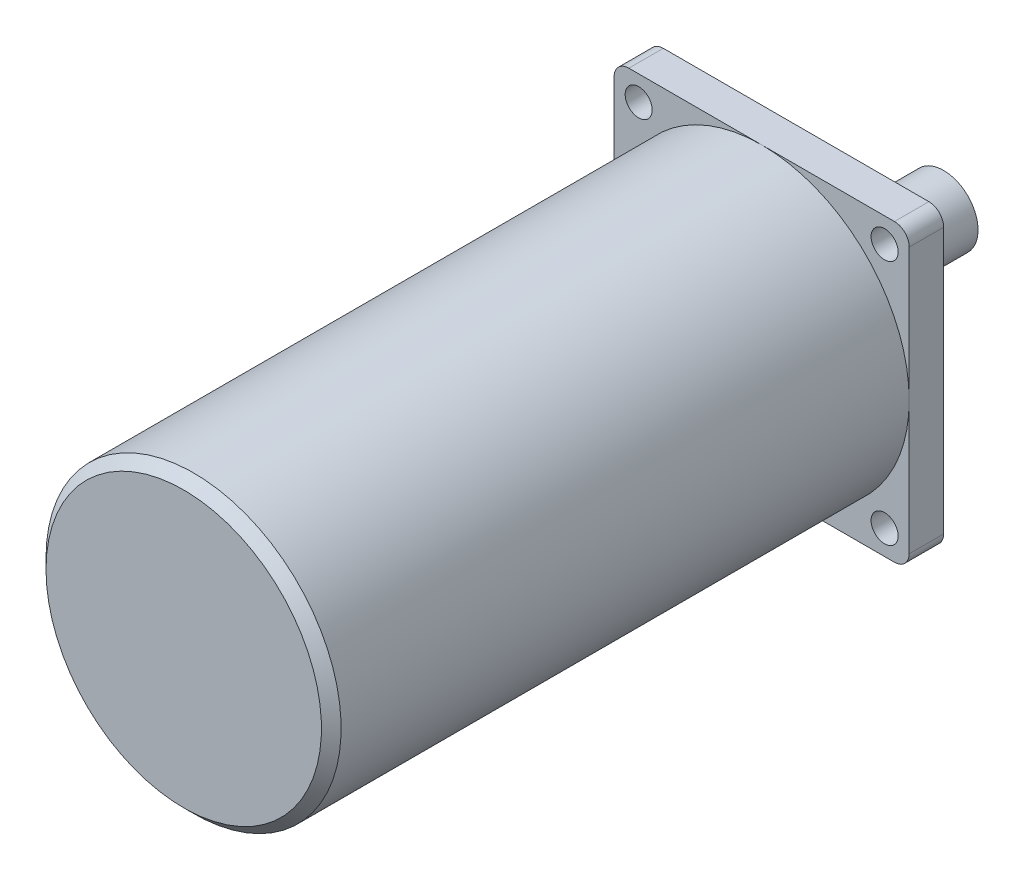
SolidWorks part; units mm, degrees
ref_plane "前基準面" through (0, 0, 0) normal (0, 0, 1) x (1, 0, 0)
ref_plane "上基準面" through (0, 0, 0) normal (0, 1, 0) x (1, 0, 0)
ref_plane "右基準面" through (0, 0, 0) normal (1, 0, 0) x (0, 0, -1)
sketch "草圖1" plane through (0, 0, 0) normal (0, 0, 1) x (1, 0, 0)
  line L1 (0, 0) -> (60, 0)
  line L2 (0, 0) -> (0, 60)
  line L3 (0, 60) -> (60, 60)
  line L4 (60, 0) -> (60, 60)
  dimension "D1" = 60
extrude "伸長1" add sketch "草圖1" along normal blind 124.5
sketch "草圖2" plane through (0, 0, 0) normal (0, 0, -1) x (-1, 0, 0)
  line L0 (-30, 60) -> (-30, 0) construction
  line L1 (-60, 60) -> (0, 60) construction
  line L2 (0, 0) -> (-60, 0) construction
  circle A0 centre (-30, 30) radius 25
  dimension "D1" = 50
extrude "伸長2" add sketch "草圖2" along normal blind 3
sketch "草圖3" plane through (0, 0, -3) normal (0, 0, -1) x (-1, 0, 0)
  circle A0 centre (-30, 30) radius 7
  dimension "D1" = 14
extrude "伸長3" add sketch "草圖3" along normal blind 27
fillet "圓角1" radius 3 4 edges at (60, 0, 62.25) (60, 60, 62.25) (0, 0, 62.25) (0, 60, 62.25)
sketch "草圖4" plane through (0, 0, 124.5) normal (0, 0, 1) x (1, 0, 0)
  line L0 (60, 3) -> (60, 57) construction
  line L1 (3, 0) -> (57, 0) construction
  line L2 (60, 3) -> (60, 30)
  line L3 (30, 0) -> (57, 0)
  line L4 (30, 0) -> (30, 60) construction
  line L5 (57, 60) -> (3, 60) construction
  line L6 (57, 3) -> (30, 30) construction
  arc A0 (57, 0) -> (60, 3) centre (57, 3) ccw construction
  arc A1 (57, 0) -> (60, 3) centre (57, 3) ccw
  arc A2 (30, 0) -> (60, 30) centre (30, 30) ccw
  dimension "D1" = 45
extrude "除料-伸長1" cut sketch "草圖4" against normal offset from surface (117.5 mm away) 7 up to face at (30, 30, 0)
pattern_circular "環狀複製排列1" count 4 every 90 of "除料-伸長1"
chamfer "導角1" distance 2 angle 45 1 edges at (60, 30, 124.5)
sketch "草圖5" plane through (0, 0, 0) normal (0, 0, -1) x (-1, 0, 0)
  line L0 (-30, 0) -> (-30, 60) construction
  line L1 (-3, 0) -> (-57, 0) construction
  line L2 (-57, 60) -> (-3, 60) construction
  line L3 (0, 30) -> (-60, 30) construction
  line L4 (0, 57) -> (0, 3) construction
  line L5 (-60, 3) -> (-60, 57) construction
  circle A0 centre (-5, 5) radius 2.75
  circle A1 centre (-55, 5) radius 2.75
  circle A2 centre (-5, 55) radius 2.75
  circle A3 centre (-55, 55) radius 2.75
  dimension "D1" = 5.5
  dimension "D2" = 50
  dimension "D3" = 50
extrude "除料-伸長2" cut sketch "草圖5" against normal through all
equation "\"D3@草圖5\" = \"D2@草圖5\""
